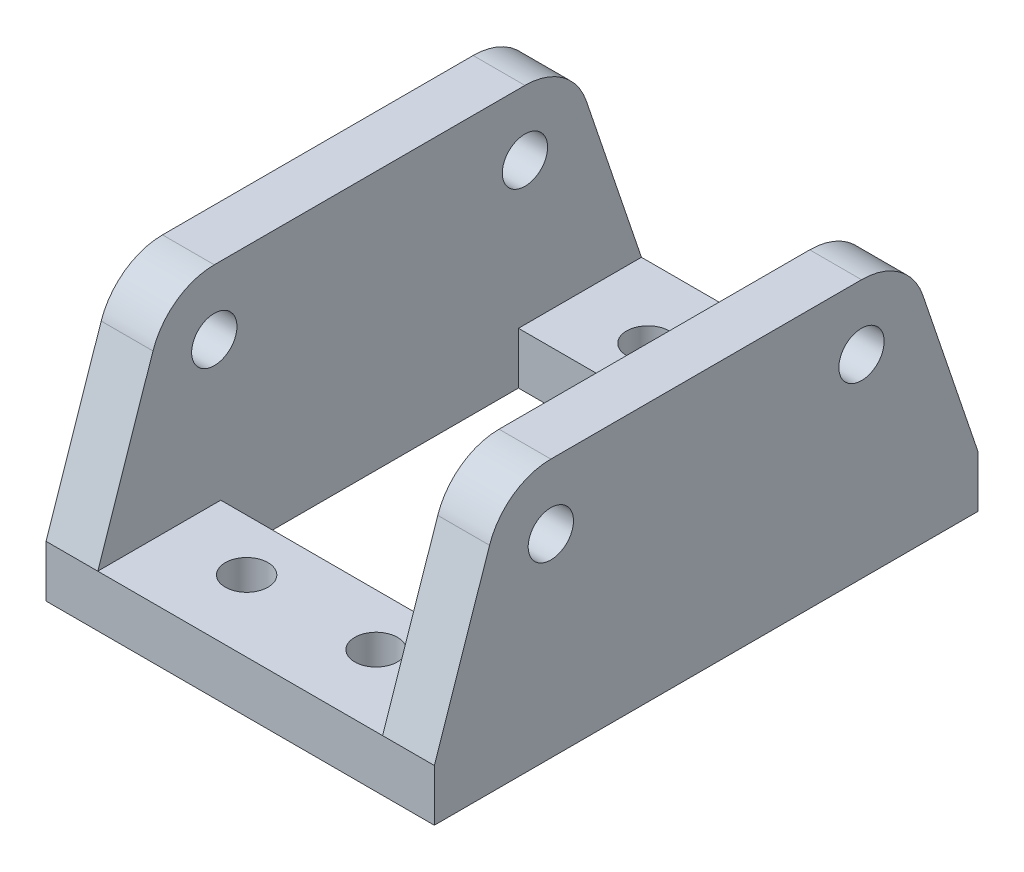
SolidWorks part; units mm, degrees
ref_plane "Plano frontal" through (0, 0, 0) normal (0, 0, 1) x (1, 0, 0)
ref_plane "Plano superior" through (0, 0, 0) normal (0, 1, 0) x (1, 0, 0)
ref_plane "Plano direito" through (0, 0, 0) normal (1, 0, 0) x (0, 0, -1)
sketch "Esboço1" plane through (0, 0, 0) normal (0, 1, 0) x (1, 0, 0)
  line L0 (-15, 25) -> (15, 25)
  line L1 (-11, 21) -> (11, 21)
  line L2 (-11, 21) -> (-11, -21)
  line L3 (-11, -21) -> (11, -21)
  line L4 (11, 21) -> (11, -21)
  line L5 (-11, 21) -> (11, -21) construction
  line L6 (-11, -21) -> (11, 21) construction
  line L7 (15, 25) -> (15, -25)
  line L8 (-15, -25) -> (15, -25)
  line L9 (-15, 25) -> (-15, -25)
  line L10 (-4, 7) -> (4, 7) construction
  line L11 (4, 7) -> (4, 17) construction
  line L12 (4, 17) -> (-4, 17) construction
  line L13 (-4, 17) -> (-4, 7) construction
  line L14 (-11, 0) -> (11, 0) construction
  line L15 (-4, -17) -> (-4, -7) construction
  line L16 (4, -17) -> (-4, -17) construction
  line L17 (4, -7) -> (4, -17) construction
  line L18 (-4, -7) -> (4, -7) construction
  point P0 (0, 0)
  point P12 (0, 7)
  dimension "D2" = 30
  dimension "D3" = 10
  dimension "D4" = 8
  dimension "D5" = 50
  dimension "D6" = 14
  dimension "D1" = 4
extrude "Ressalto-extrusão1" add sketch "Esboço1" along normal blind 20
sketch "Esboço3" plane through (15, 0, 0) normal (1, 0, 0) x (0, 0, -1)
  line L0 (0, 0) -> (0, 23.3091) construction
  line L1 (-25, 0) -> (25, 0) construction
  line L2 (-12, 15) -> (12, 15) construction
  line L3 (-25, 20) -> (25, 20) construction
  circle A0 centre (-12, 15) radius 1.75
  circle A1 centre (12, 15) radius 1.75
  circle A2 centre (-12, 15) radius 5 construction
  circle A3 centre (12, 15) radius 5 construction
  point P8 (0, 15)
  dimension "D1" = 10
  dimension "D2" = 3.5
  dimension "D3" = 14
  dimension "D4" = 5
extrude "Corte-extrusão2" cut sketch "Esboço3" against normal through all
sketch "Esboço4" plane through (0, 0, 0) normal (0, 1, 0) x (1, 0, 0)
  line L0 (0, 21) -> (0, -21) construction
  line L2 (-11, 11.5) -> (11, 11.5)
  line L4 (-11, 0) -> (11, 0) construction
  line L5 (-11, 21) -> (-11, -21) construction
  line L6 (-11, 11.5) -> (-11, 21)
  line L7 (11, -21) -> (11, 21) construction
  line L8 (-11, 21) -> (11, 21)
  line L9 (-11, -21) -> (11, -21)
  line L10 (-11, -11.5) -> (-11, -21)
  line L11 (-11, -11.5) -> (11, -11.5)
  line L12 (11, -11.5) -> (11, -21)
  line L13 (11, 11.5) -> (11, 21)
  circle A0 centre (5, -15.5) radius 1.65
  circle A1 centre (-5, 15.5) radius 1.65
  circle A2 centre (-5, -15.5) radius 1.65
  circle A3 centre (5, 15.5) radius 1.65
  point P3 (11, 21)
  point P28 (0, -11.5)
  point P31 (0, 11.5)
  dimension "D1" = 31
  dimension "D2" = 3.3
  dimension "D3" = 23
  dimension "D4" = 10
extrude "Ressalto-extrusão2" add sketch "Esboço4" along normal blind 4
sketch "Esboço5" plane through (-15, 0, 0) normal (-1, 0, 0) x (0, 0, 1)
  line L0 (-16.7363, 16.6024) -> (-21, 4)
  line L2 (-25, 0) -> (25, 0) construction
  line L3 (25, 0) -> (25, 4)
  line L4 (0, 0) -> (0, 20) construction
  line L5 (-25, 20) -> (25, 20) construction
  line L6 (21, 0) -> (25, 0)
  line L7 (-25, 20) -> (-12, 20)
  line L8 (-25, 20) -> (-25, 4)
  line L9 (21, 4) -> (21, 0)
  line L10 (25, 20) -> (25, 4)
  line L11 (25, 20) -> (12, 20)
  line L12 (-21, 4) -> (-21, 0)
  line L13 (-21, 0) -> (-25, 0)
  line L14 (-25, 0) -> (-25, 4)
  line L15 (16.7363, 16.6024) -> (21, 4)
  arc A0 (-12, 20) -> (-16.7363, 16.6024) centre (-12, 15) ccw
  arc A1 (12, 20) -> (16.7363, 16.6024) centre (12, 15) cw
  point P4 (0, 0)
  dimension "D1" = 4
  dimension "D2" = 4
extrude "Corte-extrusão3" cut sketch "Esboço5" against normal through all both and the other way through all
